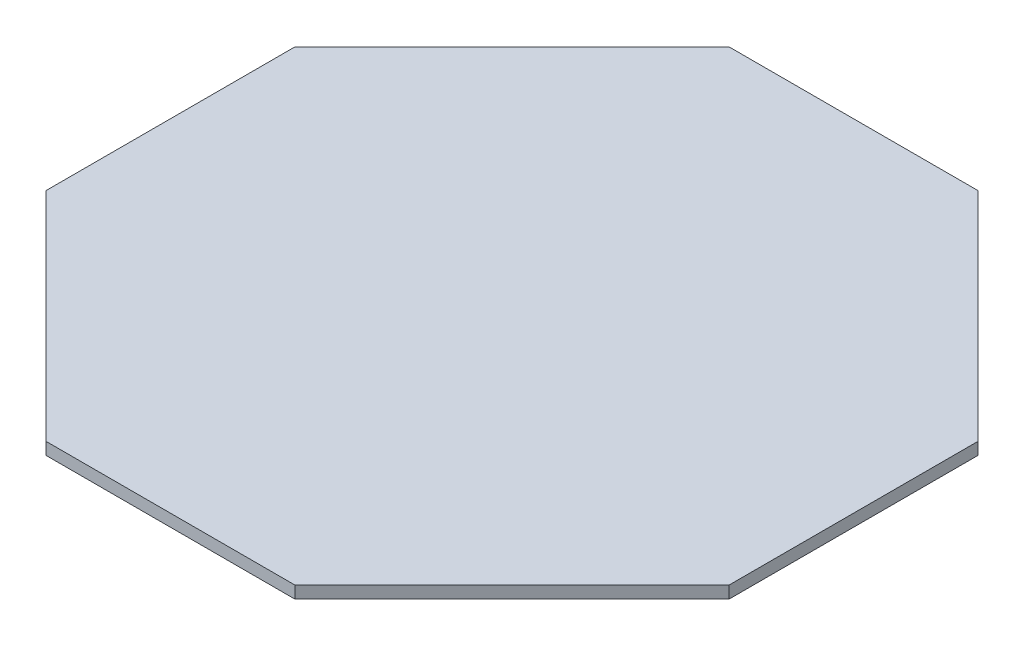
SolidWorks part; units mm, degrees
ref_plane "Front Plane" through (0, 0, 0) normal (0, 0, 1) x (1, 0, 0)
ref_plane "Top Plane" through (0, 0, 0) normal (0, 1, 0) x (1, 0, 0)
ref_plane "Right Plane" through (0, 0, 0) normal (1, 0, 0) x (0, 0, -1)
sketch "Sketch3" plane through (0, 0, 0) normal (0, 1, 0) x (1, 0, 0)
  line L9 (-612.7715, 336.2976) -> (-510.7715, 336.2976)
  line L21 (-701.7715, 145.2976) -> (-701.7715, 247.2976)
  line L23 (-421.7715, 145.2976) -> (-421.7715, 247.2976)
  line L25 (-612.7715, 56.2976) -> (-510.7715, 56.2976)
  line L31 (-701.7715, 247.2976) -> (-612.7715, 336.2976)
  line L32 (-510.7715, 336.2976) -> (-421.7715, 247.2976)
  line L33 (-701.7715, 145.2976) -> (-612.7715, 56.2976)
  line L34 (-421.7715, 145.2976) -> (-510.7715, 56.2976)
  point P21 (-561.7715, 196.2976)
extrude "Boss-Extrude1" add sketch "Sketch3" along normal blind 5
scale "Scale1" scale about centroid uniform scaling yes scale factor 0.15
